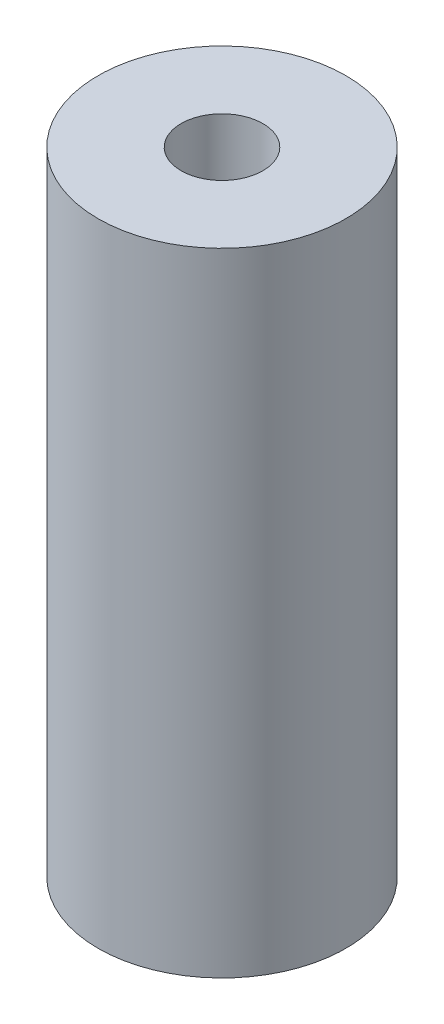
SolidWorks part; units mm, degrees
ref_plane "Спереди" through (0, 0, 0) normal (0, 0, 1) x (1, 0, 0)
ref_plane "Сверху" through (0, 0, 0) normal (0, 1, 0) x (1, 0, 0)
ref_plane "Справа" through (0, 0, 0) normal (1, 0, 0) x (0, 0, -1)
sketch "Эскиз1" plane through (0, 0, 0) normal (0, 1, 0) x (1, 0, 0)
  circle A0 centre (0, 0) radius 5
  circle A1 centre (0, 0) radius 1.65
  dimension "D1" = 10
  dimension "D2" = 3.3
extrude "Бобышка-Вытянуть1" add sketch "Эскиз1" along normal blind 25.5
